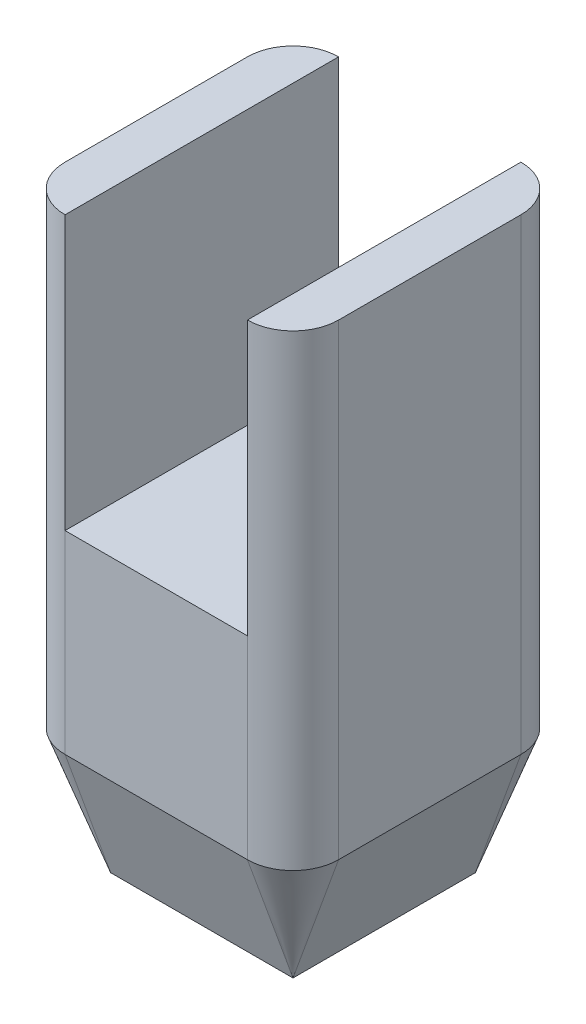
SolidWorks part; units mm, degrees
ref_plane "Front Plane" through (0, 0, 0) normal (0, 0, 1) x (1, 0, 0)
ref_plane "Top Plane" through (0, 0, 0) normal (0, 1, 0) x (1, 0, 0)
ref_plane "Right Plane" through (0, 0, 0) normal (1, 0, 0) x (0, 0, -1)
sketch "Sketch1" plane through (0, 0, 0) normal (0, 1, 0) x (1, 0, 0)
  line L0 (-1.5, 1.5) -> (1.5, -1.5) construction
  line L1 (-1.5, 1.5) -> (1.5, 1.5)
  line L2 (-1.5, 1.5) -> (-1.5, -1.5)
  line L3 (-1.5, -1.5) -> (1.5, -1.5)
  line L4 (1.5, 1.5) -> (1.5, -1.5)
  dimension "D1" = 3
extrude "Boss-Extrude1" add sketch "Sketch1" along normal blind 3.5
fillet "Fillet1" radius 0.5 4 edges at (-1.5, 1.75, -1.5) (1.5, 1.75, -1.5) (-1.5, 1.75, 1.5) (1.5, 1.75, 1.5)
chamfer "Chamfer1" distance 0.5 angle 70 8 edges at (0, 0, -1.5) (-1.3536, 0, -1.3536) (1.3536, 0, -1.3536) (-1.5, 0, 0) (1.5, 0, 0) (-1.3536, 0, 1.3536) (1.3536, 0, 1.3536) (0, 0, 1.5)
sketch "Sketch2" plane through (0, 3.5, 0) normal (0, 1, 0) x (1, 0, 0)
  line L2 (-1, 1.5) -> (-1, -1.5)
  line L4 (1, 1.5) -> (-1, 1.5)
  line L5 (-1.5, 1) -> (-1.5, -1)
  line L6 (-1, -1.5) -> (1, -1.5)
  line L7 (1.5, -1) -> (1.5, 1)
  line L9 (-1.5, 1) -> (-1.5, -1)
  line L11 (1.5, -1) -> (1.5, 1)
  line L12 (1, 1.5) -> (1, -1.5)
  arc A4 (-1, 1.5) -> (-1.5, 1) centre (-1, 1) ccw
  arc A5 (-1.5, -1) -> (-1, -1.5) centre (-1, -1) ccw
  arc A6 (1, -1.5) -> (1.5, -1) centre (1, -1) ccw
  arc A7 (1.5, 1) -> (1, 1.5) centre (1, 1) ccw
  arc A8 (-1, 1.5) -> (-1.5, 1) centre (-1, 1) ccw
  arc A9 (-1.5, -1) -> (-1, -1.5) centre (-1, -1) ccw
  arc A10 (1, -1.5) -> (1.5, -1) centre (1, -1) ccw
  arc A11 (1.5, 1) -> (1, 1.5) centre (1, 1) ccw
  dimension "D1" = 0
extrude "Boss-Extrude2" add sketch "Sketch2" along normal blind 3
